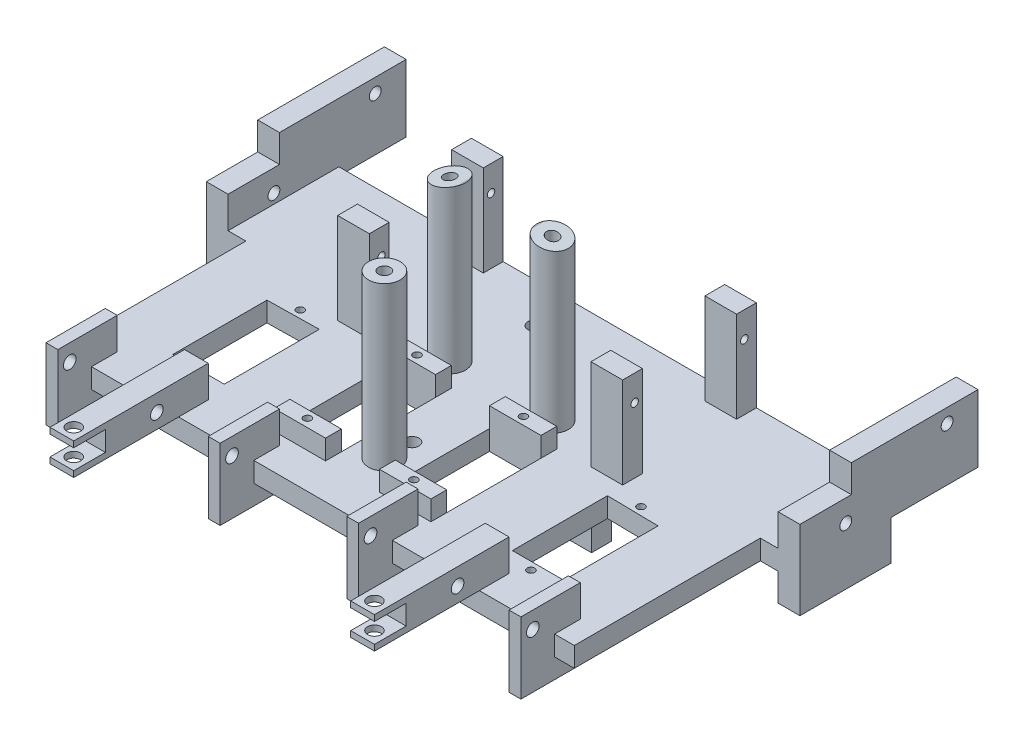
SolidWorks part; units mm, degrees
material "PMMA"
ref_plane "前视基准面" through (0, 0, 0) normal (0, 0, 1) x (1, 0, 0)
ref_plane "上视基准面" through (0, 0, 0) normal (0, 1, 0) x (1, 0, 0)
ref_plane "右视基准面" through (0, 0, 0) normal (1, 0, 0) x (0, 0, -1)
sketch "草图1" plane through (0, 0, 0) normal (0, 1, 0) x (1, 0, 0)
  line L1 (-65, 37.5) -> (65, 37.5)
  line L2 (-65, 37.5) -> (-65, -37.5)
  line L3 (-65, -37.5) -> (65, -37.5)
  line L4 (65, 37.5) -> (65, -37.5)
  line L5 (-65, 37.5) -> (65, -37.5) construction
  line L6 (-65, -37.5) -> (65, 37.5) construction
  point P0 (0, 0)
  dimension "D1" = 130
  dimension "D2" = 75
extrude "凸台-拉伸1" add sketch "草图1" along normal blind 5
sketch "草图4" plane through (0, 5, 0) normal (0, 1, 0) x (1, 0, 0)
  line L1 (-69.5, 9.5) -> (69.5, 9.5)
  line L2 (-69.5, 9.5) -> (-69.5, 37.5)
  line L3 (-69.5, 37.5) -> (69.5, 37.5)
  line L4 (69.5, 9.5) -> (69.5, 37.5)
  line L5 (-69.5, 9.5) -> (69.5, 37.5) construction
  line L6 (-69.5, 37.5) -> (69.5, 9.5) construction
  line L7 (-65, -37.5) -> (65, -37.5) construction
  point P0 (0, 23.5)
  dimension "D1" = 139
  dimension "D2" = 28
  dimension "D3" = 75
extrude "凸台-拉伸4" add sketch "草图4" against normal blind 5
sketch "草图5" plane through (-69.5, 0, 0) normal (-1, 0, 0) x (0, 0, 1)
  line L0 (-37.5, 5) -> (-9.5, 5) construction
  line L1 (-9.5, 13) -> (-32.5, 13)
  line L2 (-9.5, 13) -> (-9.5, -7)
  line L3 (-9.5, -7) -> (-32.5, -7)
  line L4 (-32.5, 13) -> (-32.5, -7)
  line L5 (-9.5, 5) -> (-9.5, 0) construction
  dimension "D1" = 8
  dimension "D2" = 23
  dimension "D3" = 20
extrude "凸台-拉伸5" add sketch "草图5" along normal blind 5.5
sketch "草图18" plane through (0, 0, 0) normal (0, -1, 0) x (1, 0, 0)
  line L0 (-75, -32.5) -> (-69.5, -32.5) construction
  line L1 (-69.5, -9.5) -> (-63, -9.5)
  line L2 (-69.5, -9.5) -> (-69.5, -32.5)
  line L3 (-69.5, -32.5) -> (-63, -32.5)
  line L4 (-63, -9.5) -> (-63, -32.5)
  line L5 (-75, -32.5) -> (-75, -9.5) construction
  dimension "D1" = 12
sketch "草图6" plane through (-69.5, 0, 0) normal (-1, 0, 0) x (0, 0, 1)
  line L1 (-54.5, 20) -> (-22.5, 20)
  line L2 (-54.5, 20) -> (-54.5, 3)
  line L3 (-54.5, 3) -> (-22.5, 3)
  line L4 (-22.5, 20) -> (-22.5, 3)
  line L5 (-37.5, 5) -> (-32.5, 5) construction
  line L6 (-37.5, 0) -> (-37.5, 5) construction
  dimension "D1" = 15
  dimension "D2" = 17
  dimension "D3" = 32
  dimension "D4" = 17
extrude "凸台-拉伸6" add sketch "草图6" along normal blind 5.5
sketch "草图8" plane through (0, 5, 0) normal (0, 1, 0) x (1, 0, 0)
  line L0 (69.5, 37.5) -> (-69.5, 37.5) construction
  line L1 (-36, 37.5) -> (-28, 37.5)
  line L2 (-36, 37.5) -> (-36, 32.5)
  line L3 (-36, 32.5) -> (-28, 32.5)
  line L4 (-28, 37.5) -> (-28, 32.5)
  line L6 (-36, 8.7) -> (-28, 8.7)
  line L7 (-36, 8.7) -> (-36, 3.7)
  line L8 (-36, 3.7) -> (-28, 3.7)
  line L9 (-28, 8.7) -> (-28, 3.7)
  dimension "D1" = 23.8
  dimension "D2" = 36
  dimension "D3" = 8
  dimension "D4" = 5
  dimension "D5" = 5
extrude "凸台-拉伸7" add sketch "草图8" along normal blind 23
sketch "草图9" plane through (0, 5, 0) normal (0, 1, 0) x (1, 0, 0)
  line L1 (-19, -31) -> (-16, -31)
  line L2 (-19, -31) -> (-19, -46)
  line L3 (-19, -46) -> (-16, -46)
  line L4 (-16, -31) -> (-16, -46)
  dimension "D1" = 19
  dimension "D2" = 3
  dimension "D3" = 15
  dimension "D4" = 46
extrude "凸台-拉伸8" add sketch "草图9" along normal blind 8 and the other way blind 10
sketch "草图10" plane through (0, 5, 0) normal (0, 1, 0) x (1, 0, 0)
  line L0 (-19, -31) -> (-19, -46) construction
  line L1 (-60, -31) -> (-57, -31)
  line L2 (-60, -31) -> (-60, -46)
  line L3 (-60, -46) -> (-57, -46)
  line L4 (-57, -31) -> (-57, -46)
  line L6 (-16, -31) -> (-19, -31) construction
  line L7 (-19, -46) -> (-16, -46) construction
  dimension "D1" = 38
extrude "凸台-拉伸9" add sketch "草图10" along normal blind 8 and the other way blind 10
sketch "草图11" plane through (0, 5, 0) normal (0, 1, 0) x (1, 0, 0)
  line L1 (-41, -30) -> (-35, -30)
  line L2 (-41, -30) -> (-41, -64)
  line L3 (-41, -64) -> (-35, -64)
  line L4 (-35, -30) -> (-35, -64)
  dimension "D1" = 6
  dimension "D2" = 34
  dimension "D3" = 64
  dimension "D4" = 35
extrude "凸台-拉伸10" add sketch "草图11" along normal blind 8
sketch "草图12" plane through (0, 5, 0) normal (0, 1, 0) x (1, 0, 0)
  circle A0 centre (-13, 9) radius 4
  dimension "D1" = 13
  dimension "D2" = 9
  dimension "D3" = 8
extrude "凸台-拉伸11" add sketch "草图12" along normal blind 41
sketch "草图19" plane through (-36, 0, 0) normal (-1, 0, 0) x (0, 0, 1)
  line L1 (-8.7, 28) -> (-8.7, 5) construction
  line L2 (-8.7, 28) -> (-3.7, 28) construction
  line L3 (-32.5, 28) -> (-32.5, 5) construction
  circle A0 centre (-6.75, 21.5) radius 0.95
  circle A1 centre (-34.45, 21.5) radius 0.95
  dimension "D1" = 6.5
  dimension "D2" = 1.95
  dimension "D3" = 1.9
  dimension "D4" = 27.7
  dimension "D5" = 1.9
  dimension "D6" = 1.95
extrude "切除-拉伸8" cut sketch "草图19" against normal up to next
sketch "草图25" plane through (0, 5, 0) normal (0, 1, 0) x (1, 0, 0)
  circle A0 centre (0, -20.5) radius 4
  circle A1 centre (-13, 9) radius 4 construction
  dimension "D1" = 20.5
extrude "凸台-拉伸14" add sketch "草图25" along normal blind 41
sketch "草图26" plane through (0, 0, 0) normal (0, 0, 1) x (1, 0, 0)
  line L0 (-17, 46) -> (-17, 44.644)
  line L1 (-17, 46) -> (-17, 5) construction
  line L2 (-17, 44.644) -> (-9.31, 46)
  line L3 (-9, 46) -> (-17, 46) construction
  line L4 (-9.31, 46) -> (-17, 46)
  dimension "D1" = 10
  dimension "D2" = 0.31
extrude "切除-拉伸14" cut sketch "草图26" against normal blind 36
sketch "草图28" plane through (0, 0, 64) normal (0, 0, 1) x (1, 0, 0)
  line L0 (-41, 13) -> (-41, 5) construction
  line L1 (-41, 11.5) -> (-35, 11.5)
  line L2 (-41, 11.5) -> (-41, 6.5)
  line L3 (-41, 6.5) -> (-35, 6.5)
  line L4 (-35, 11.5) -> (-35, 6.5)
  line L5 (-35, 13) -> (-35, 5) construction
  line L6 (-41, 13) -> (-35, 13) construction
  dimension "D1" = 1.5
  dimension "D2" = 5
extrude "切除-拉伸16" cut sketch "草图28" against normal blind 8
sketch "草图29" plane through (0, 13, 0) normal (0, 1, 0) x (1, 0, 0)
  line L0 (-41, -64) -> (-35, -64) construction
  circle A0 centre (-38, -61) radius 1.75
  point P5 (-38, -64)
  dimension "D1" = 3
  dimension "D2" = 3.5
extrude "切除-拉伸17" cut sketch "草图29" against normal blind 8
sketch "草图30" plane through (-60, 0, 0) normal (-1, 0, 0) x (0, 0, 1)
  line L0 (31, 5) -> (37.5, 5) construction
  circle A0 centre (43, 8.75) radius 1.6
  dimension "D1" = 43
  dimension "D2" = 3.75
  dimension "D3" = 3.2
extrude "切除-拉伸18" cut sketch "草图30" against normal blind 48
sketch "草图31" plane through (0, 5, 0) normal (0, 1, 0) x (1, 0, 0)
  circle A0 centre (0, -13.5) radius 1.75
  circle A1 centre (-10, 27.5) radius 1.75
  circle A2 centre (10, 27.5) radius 1.75
  dimension "D1" = 20
  dimension "D2" = 10
  dimension "D3" = 27.5
  dimension "D4" = 3.5
  dimension "D5" = 3.5
  dimension "D7" = 3.5
  dimension "D6" = 13.5
extrude "切除-拉伸19" cut sketch "草图31" against normal blind 20
sketch "草图35" plane through (-75, 0, 0) normal (-1, 0, 0) x (0, 0, 1)
  circle A0 centre (-46.6884, 16.4527) radius 1.5
  circle A1 centre (-21.0894, 7.4378) radius 1.5
  dimension "D1" = 3
  dimension "D2" = 3
extrude "切除-拉伸23" cut sketch "草图35" against normal blind 15
sketch "草图36" plane through (0, 5, 0) normal (0, 1, 0) x (1, 0, 0)
  line L0 (-13.4508, 4.0639) -> (-13.4508, -27.9765) construction
  line L1 (-19.8158, -0.7564) -> (-6.8158, -0.7564)
  line L2 (-19.8158, -0.7564) -> (-19.8158, -24.5564)
  line L3 (-19.8158, -24.5564) -> (-6.8158, -24.5564)
  line L4 (-6.8158, -0.7564) -> (-6.8158, -24.5564)
  line L5 (-36.4092, -0.5409) -> (-36.4092, -24.5564)
  line L6 (-43.043, 4.4976) -> (-43.043, -27.5429) construction
  line L7 (-49.408, -24.5564) -> (-36.4092, -24.5564)
  line L8 (-49.4074, -0.7564) -> (-49.408, -24.5564)
  line L9 (-49.4074, -0.7564) -> (-36.4092, -0.5409)
  circle A0 centre (-13.4508, 1.1936) radius 0.95
  circle A1 centre (-13.4508, -26.5064) radius 0.95
  circle A2 centre (-43.043, -26.5064) radius 0.95
  circle A3 centre (-43.0421, 1.2994) radius 0.95
  dimension "D3" = 1.9
  dimension "D4" = 1.9
  dimension "D9" = 1.9
  dimension "D10" = 1.9
  dimension "D1" = 23.8
  dimension "D2" = 13
  dimension "D5" = 1.95
  dimension "D6" = 1.95
  dimension "D7" = 23.8
  dimension "D8" = 13
  dimension "D11" = 1.95
  dimension "D12" = 1.95
extrude "切除-拉伸24" cut sketch "草图36" against normal blind 7
sketch "草图37" plane through (0, 0, 0) normal (0, -1, 0) x (1, 0, 0)
  line L1 (-23.5802, -36.7581) -> (-29.5802, -36.7581)
  line L2 (-23.5802, -36.7581) -> (-23.5802, -31.7581)
  line L3 (-23.5802, -31.7581) -> (-29.5802, -31.7581)
  line L4 (-29.5802, -36.7581) -> (-29.5802, -31.7581)
  line L5 (-23.5802, -7.9581) -> (-28.8866, -7.9581)
  line L6 (-23.5802, -7.9581) -> (-23.5802, -2.9581)
  line L7 (-23.5802, -2.9581) -> (-28.8866, -2.9581)
  line L8 (-28.8866, -7.9581) -> (-28.8866, -2.9581)
  dimension "D1" = 23.8
  dimension "D2" = 6
  dimension "D3" = 5
  dimension "D4" = 5
extrude "凸台-拉伸15" add sketch "草图37" along normal blind 13
sketch "草图38" plane through (-29.5802, 0, 0) normal (-1, 0, 0) x (0, 0, 1)
  line L0 (-31.7581, -13) -> (-31.7581, 0) construction
  line L2 (-37.5, 0) -> (-32.5, 0) construction
  line L3 (-19.8581, 2.1642) -> (-19.8581, -15.8009) construction
  circle A0 centre (-33.7081, -4.5) radius 0.95
  circle A1 centre (-6.0081, -4.5) radius 0.95
  dimension "D1" = 1.9
  dimension "D2" = 1.95
  dimension "D3" = 4.5
  dimension "D4" = 11.9
extrude "切除-拉伸25" cut sketch "草图38" against normal blind 13
sketch "草图43" plane through (0, 0, 0) normal (0, -1, 0) x (1, 0, 0)
  line L0 (69.5, -37.5) -> (-69.5, -37.5) construction
  line L1 (-52.8866, -0.9581) -> (-15.5802, -0.9581)
  line L2 (-52.8866, -0.9581) -> (-52.8866, -37.5)
  line L3 (-52.8866, -37.5) -> (-15.5802, -37.5)
  line L4 (-15.5802, -0.9581) -> (-15.5802, -37.5)
  line L5 (-23.5802, -2.9581) -> (-28.8866, -2.9581) construction
  line L6 (-23.5802, -7.9581) -> (-23.5802, -2.9581) construction
  line L7 (-23.5802, -2.9581) -> (-28.8866, -2.9581) construction
  line L8 (-28.8866, -2.9581) -> (-28.8866, -7.9581) construction
  line L9 (-28.8866, -7.9581) -> (-23.5802, -7.9581) construction
  line L10 (-23.5802, -36.7581) -> (-23.5802, -31.7581) construction
  line L11 (-23.5802, -31.7581) -> (-29.5802, -31.7581) construction
  line L12 (-29.5802, -31.7581) -> (-29.5802, -36.7581) construction
  line L13 (-29.5802, -36.7581) -> (-23.5802, -36.7581) construction
  line L14 (-23.5802, -7.9581) -> (-23.5802, -2.9581)
  line L15 (-23.5802, -2.9581) -> (-28.8866, -2.9581)
  line L16 (-28.8866, -2.9581) -> (-28.8866, -7.9581)
  line L17 (-28.8866, -7.9581) -> (-23.5802, -7.9581)
  line L18 (-23.5802, -36.7581) -> (-23.5802, -31.7581)
  line L19 (-23.5802, -31.7581) -> (-29.5802, -31.7581)
  line L20 (-29.5802, -31.7581) -> (-29.5802, -36.7581)
  line L21 (-29.5802, -36.7581) -> (-23.5802, -36.7581)
  dimension "D1" = 2
  dimension "D2" = 8
  dimension "D3" = 24
extrude "切除-拉伸28" cut sketch "草图43" against normal blind 2
sketch "草图41" plane through (0, 5, 0) normal (0, 1, 0) x (1, 0, 0)
  line L0 (-19.8158, -0.7564) -> (-19.8158, -24.5564) construction
  line L1 (-6.8158, -0.7564) -> (-19.8158, -0.7564)
  line L2 (-6.8158, -0.7564) -> (-6.8158, 3.2436)
  line L3 (-6.8158, 3.2436) -> (-19.8158, 3.2436)
  line L4 (-19.8158, -0.7564) -> (-19.8158, 3.2436)
  line L5 (-6.8158, -24.5564) -> (-6.8158, -0.7564) construction
  line L6 (-19.8158, -24.5564) -> (-6.8158, -24.5564)
  line L7 (-19.8158, -24.5564) -> (-19.8158, -28.5564)
  line L8 (-19.8158, -28.5564) -> (-6.8158, -28.5564)
  line L9 (-6.8158, -24.5564) -> (-6.8158, -28.5564)
  circle A0 centre (-13.4508, 1.1936) radius 0.95
  circle A1 centre (-13.4508, -26.5064) radius 0.95
  dimension "D3" = 1.9
  dimension "D4" = 1.9
  dimension "D1" = 4
  dimension "D2" = 4
extrude "凸台-拉伸16" add sketch "草图41" along normal blind 5
sketch "草图39" plane through (0, 5, 0) normal (0, 1, 0) x (1, 0, 0)
  circle A0 centre (-13, 9) radius 1.5
  circle A1 centre (0, -20.5) radius 1.5
  dimension "D1" = 3
  dimension "D2" = 3
extrude "切除-拉伸26" cut sketch "草图39" against normal blind 13 and the other way blind 42
mirror "镜向1" about plane through (0, 0, 0) normal (1, 0, 0) of "凸台-拉伸16", "切除-拉伸26", "切除-拉伸25", "凸台-拉伸15", "切除-拉伸24", "切除-拉伸23", "切除-拉伸19", "切除-拉伸18", "切除-拉伸17", "切除-拉伸16", "切除-拉伸14", "凸台-拉伸14", "切除-拉伸8", "凸台-拉伸11", "凸台-拉伸10", "凸台-拉伸9", "凸台-拉伸8", "凸台-拉伸7", "凸台-拉伸6", "凸台-拉伸5", "切除-拉伸28"
